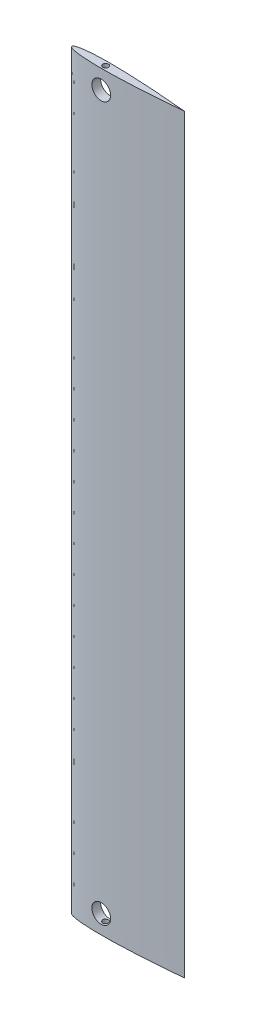
SolidWorks part; units mm, degrees
ref_plane "Front" through (0, 0, 0) normal (0, 0, 1) x (1, 0, 0)
ref_plane "Top" through (0, 0, 0) normal (0, 1, 0) x (1, 0, 0)
ref_plane "Right" through (0, 0, 0) normal (1, 0, 0) x (0, 0, -1)
sketch "草图1" plane through (0, 0, 0) normal (0, 1, 0) x (1, 0, 0)
  line L0 (-17.327, 0) -> (78.6979, 0) construction
  spline S0 degree 4 poles (0, 0) (0.0001, 0.0347) (0.005, 0.0797) (0.0197, 0.1365) (0.0508, 0.2076) (0.0827, 0.2634) (0.1297, 0.328) (0.1999, 0.4047) (0.3032, 0.4955) (0.467, 0.6107) (0.7462, 0.7652) (1.2617, 0.9816) (2.242, 1.2784) (4.1466, 1.6668) (7.0965, 2.0285) (10.9568, 2.2879) (15.4789, 2.4108) (20.1752, 2.4083) (24.868, 2.3117) (29.5627, 2.1442) (33.662, 1.9502) (37.1847, 1.7552) (40.1028, 1.5779) (42.4659, 1.424) (44.7701, 1.2668) (47.1734, 1.0915) (49.9884, 0.8797) (53.1116, 0.6235) (55.7211, 0.4016) (59.2803, 0.0714) (60.9796, -0.0941) (63.3759, -0.3366) (64.5782, -0.4676) (65.5155, -0.5675) (65.7644, -0.5967) (66.0124, -0.6233) knots 0 0 0 0 0 0.002066 0.002722 0.003494 0.004655 0.00591 0.007512 0.009724 0.012895 0.017904 0.026634 0.043223 0.074288 0.134449 0.204906 0.275363 0.34582 0.416277 0.486734 0.557191 0.592419 0.627648 0.662876 0.698105 0.733333 0.768562 0.839019 0.874247 0.909476 0.954738 0.977369 0.988684 1 1 1 1 1 construction
  spline S1 degree 4 poles (0, 0) (0.0001, 0.0347) (0.005, 0.0797) (0.0197, 0.1365) (0.0508, 0.2076) (0.0827, 0.2634) (0.1297, 0.328) (0.1999, 0.4047) (0.3032, 0.4955) (0.467, 0.6107) (0.7462, 0.7652) (1.2617, 0.9816) (2.242, 1.2784) (4.1466, 1.6668) (7.0965, 2.0285) (10.9568, 2.2879) (15.4789, 2.4108) (20.1752, 2.4083) (24.868, 2.3117) (29.5627, 2.1442) (33.662, 1.9502) (37.1847, 1.7552) (40.1028, 1.5779) (42.4659, 1.424) (44.7701, 1.2668) (47.1734, 1.0915) (49.9884, 0.8797) (53.1116, 0.6235) (55.7211, 0.4016) (58.415, 0.1517) (59.4687, 0.0515) (60, 0) knots 0 0 0 0 0 0.002066 0.002722 0.003494 0.004655 0.00591 0.007512 0.009724 0.012895 0.017904 0.026634 0.043223 0.074288 0.134449 0.204906 0.275363 0.34582 0.416277 0.486734 0.557191 0.592419 0.627648 0.662876 0.698105 0.733333 0.768562 0.839019 0.874247 0.909476 0.909476 0.909476 0.909476 0.909476
  spline S2 degree 4 poles (0, 0) (0.0001, -0.0347) (0.005, -0.0797) (0.0197, -0.1365) (0.0508, -0.2076) (0.0827, -0.2634) (0.1297, -0.328) (0.1999, -0.4047) (0.3032, -0.4955) (0.467, -0.6107) (0.7462, -0.7652) (1.2617, -0.9816) (2.242, -1.2784) (4.1466, -1.6668) (7.0965, -2.0285) (10.9568, -2.2879) (15.4789, -2.4108) (20.1752, -2.4083) (24.868, -2.3117) (29.5627, -2.1442) (33.662, -1.9502) (37.1847, -1.7552) (40.1028, -1.5779) (42.4659, -1.424) (44.7701, -1.2668) (47.1734, -1.0915) (49.9884, -0.8797) (53.1116, -0.6235) (55.7211, -0.4016) (58.415, -0.1517) (59.4687, -0.0515) (60, 0) knots 0 0 0 0 0 0.002066 0.002722 0.003494 0.004655 0.00591 0.007512 0.009724 0.012895 0.017904 0.026634 0.043223 0.074288 0.134449 0.204906 0.275363 0.34582 0.416277 0.486734 0.557191 0.592419 0.627648 0.662876 0.698105 0.733333 0.768562 0.839019 0.874247 0.909476 0.909476 0.909476 0.909476 0.909476
  point P7 (78.6979, 0)
  point P8 (-30.3935, 15.3028)
extrude "凸台-拉伸1" add sketch "草图1" along normal blind 200
sketch "草图3" plane through (0, 0, 0) normal (0, 0, 1) x (1, 0, 0)
  line L0 (-15.8506, 0) -> (82.5005, 0) construction
  line L1 (0, -16.4516) -> (0, 121.3816) construction
  line L2 (0, 200) -> (0, 0) construction
  circle A0 centre (18, 10) radius 5
  dimension "D1" = 18
  dimension "D2" = 10
  dimension "D3" = 10
extrude "切除-拉伸1" cut sketch "草图3" against normal mid plane 40
sketch "草图4" plane through (0, 0, 0) normal (0, -1, 0) x (1, 0, 0)
  line L0 (-8.4834, 0) -> (72.5012, 0) construction
  circle A0 centre (18, 0) radius 1.5
  dimension "D1" = 3
  dimension "D2" = 18
extrude "切除-拉伸2" cut sketch "草图4" against normal blind 10
mirror "镜向1" about plane through (29.7759, 200, 2.1239) normal (0, -1, 0) of "凸台-拉伸1", "切除-拉伸1", "切除-拉伸2"
